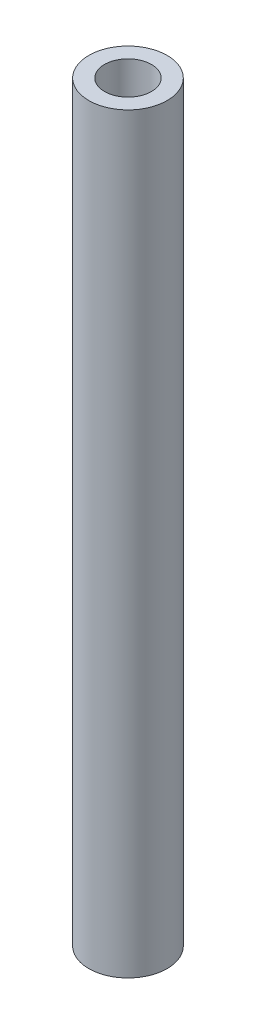
SolidWorks part; units mm, degrees
ref_plane "前视基准面" through (0, 0, 0) normal (0, 0, 1) x (1, 0, 0)
ref_plane "上视基准面" through (0, 0, 0) normal (0, 1, 0) x (1, 0, 0)
ref_plane "右视基准面" through (0, 0, 0) normal (1, 0, 0) x (0, 0, -1)
sketch "草图1" plane through (0, 0, 0) normal (0, 1, 0) x (1, 0, 0)
  circle A0 centre (0, 0) radius 2.5
  circle A1 centre (0, 0) radius 1.5
  dimension "D1" = 3
  dimension "D2" = 5
extrude "凸台-拉伸1" add sketch "草图1" along normal blind 48
